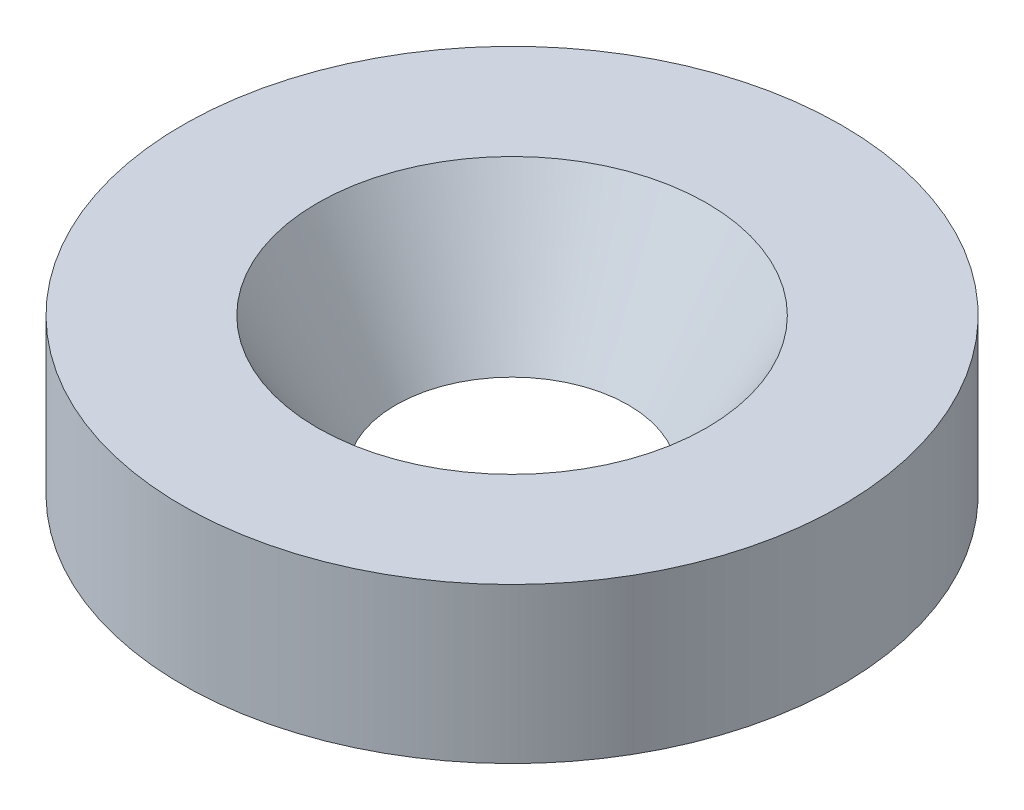
SolidWorks part; units mm, degrees
ref_plane "Front Plane" through (0, 0, 0) normal (0, 0, 1) x (1, 0, 0)
ref_plane "Top Plane" through (0, 0, 0) normal (0, 1, 0) x (1, 0, 0)
ref_plane "Right Plane" through (0, 0, 0) normal (1, 0, 0) x (0, 0, -1)
sketch "Sketch1" plane through (0, 0, 0) normal (0, 0, 1) x (1, 0, 0)
  line L0 (10.1924, 0) -> (0, 0) construction
  line L1 (0, 0) -> (0, 15.1078) construction
  line L2 (8.5, 0) -> (8.5, 4)
  line L3 (8.5, 4) -> (5.0207, 4)
  line L4 (5.0207, 4) -> (3, 0.5)
  line L5 (3, 0.5) -> (6, 0.5)
  line L6 (6, 0.5) -> (6, 2.75)
  line L7 (6, 2.75) -> (8, 2.75)
  line L8 (8, 2.75) -> (8, 0)
  line L9 (8, 0) -> (8.5, 0)
  dimension "D1" = 2
  dimension "D2" = 2.25
  dimension "D3" = 0.5
  dimension "D4" = 1.25
  dimension "D5" = 4
  dimension "D6" = 60
  dimension "D7" = 3
  dimension "D8" = 8.5
revolve "Revolve1" add sketch "Sketch1" angle 360 about L1
